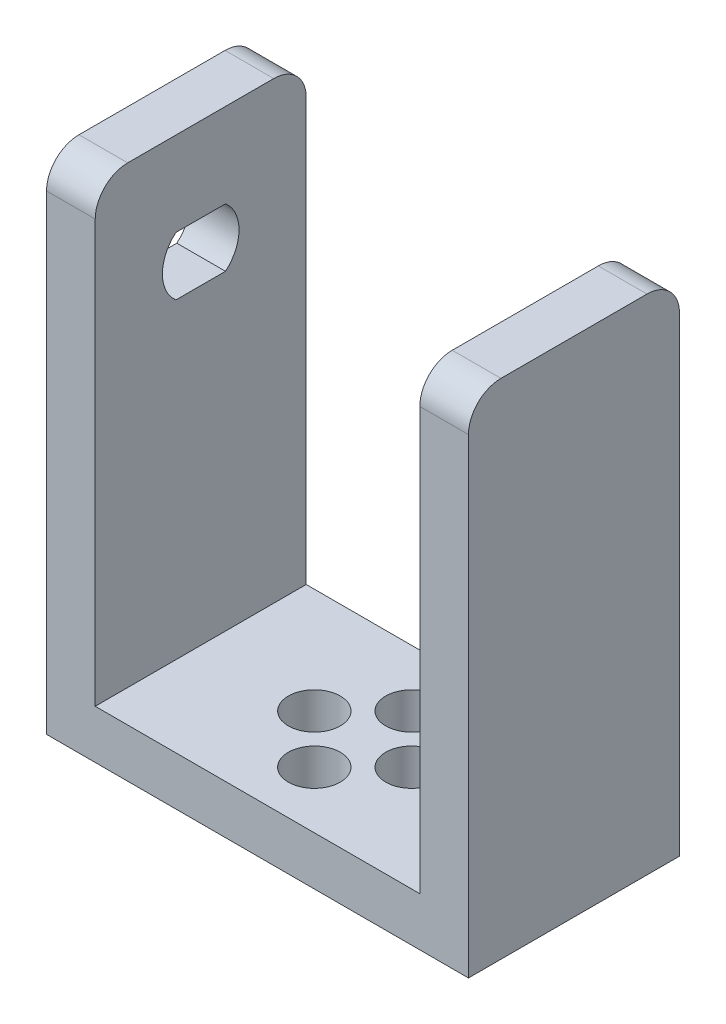
SolidWorks part; units mm, degrees
ref_plane "前视基准面" through (0, 0, 0) normal (0, 0, 1) x (1, 0, 0)
ref_plane "上视基准面" through (0, 0, 0) normal (0, 1, 0) x (1, 0, 0)
ref_plane "右视基准面" through (0, 0, 0) normal (1, 0, 0) x (0, 0, -1)
sketch "草图1" plane through (0, 0, 0) normal (0, 1, 0) x (1, 0, 0)
  line L0 (0, 0) -> (6.5796, 0) construction
  line L1 (-10, -6.5) -> (10, -6.5)
  line L2 (-10, -6.5) -> (-10, 6.5)
  line L3 (-10, 6.5) -> (10, 6.5)
  line L4 (10, -6.5) -> (10, 6.5)
  line L5 (-10, -6.5) -> (10, 6.5) construction
  line L6 (-10, 6.5) -> (10, -6.5) construction
  line L7 (0, 0) -> (0, 5.5116) construction
  circle A0 centre (0, 3) radius 1.6
  circle A1 centre (3, 0) radius 1.6
  circle A2 centre (0, -3) radius 1.6
  circle A3 centre (-3, 0) radius 1.6
  point P0 (0, 0)
  dimension "D3" = 3
  dimension "D1" = 13
  dimension "D2" = 20
  dimension "D4" = 3
extrude "凸台-拉伸1" add sketch "草图1" along normal blind 3
sketch "草图2" plane through (0, 0, 0) normal (0, 1, 0) x (1, 0, 0)
  line L0 (13, 6.5) -> (13, -6.5)
  line L1 (0, 0) -> (0, 7.5299) construction
  line L2 (10, 6.5) -> (10, 7.8287) construction
  line L3 (10, 6.5) -> (13, 6.5)
  line L4 (10, -6.5) -> (13, -6.5)
  line L5 (-10, -6.5) -> (-13, -6.5)
  line L6 (-13, 6.5) -> (-13, -6.5)
  line L7 (-10, 6.5) -> (-13, 6.5)
  line L8 (-10, 6.5) -> (-10, -6.5)
  line L9 (10, 6.5) -> (10, -6.5)
  dimension "D1" = 3
extrude "凸台-拉伸2" add sketch "草图2" along normal blind 31
sketch "草图3" plane through (10, 0, 0) normal (-1, 0, 0) x (0, 0, 1)
  line L0 (6.5, 0) -> (-6.5, 0) construction
  circle A0 centre (0, 24) radius 4.13
  dimension "D1" = 24
extrude "切除-拉伸1" cut sketch "草图3" against normal blind 1.5
sketch "草图4" plane through (-10, 0, 0) normal (1, 0, 0) x (0, 0, -1)
  line L0 (6.5, 0) -> (-6.5, 0) construction
  line L1 (1.5263, 25.8) -> (-1.5263, 25.8)
  line L2 (0, 24) -> (-1.5027, 24) construction
  line L3 (1.5263, 22.2) -> (-1.5263, 22.2)
  arc A0 (-1.5263, 25.8) -> (-1.5263, 22.2) centre (0, 24) ccw
  arc A1 (1.5263, 22.2) -> (1.5263, 25.8) centre (0, 24) ccw
  dimension "D2" = 1.8
  dimension "D3" = 1.8
  dimension "D1" = 24
extrude "切除-拉伸2" cut sketch "草图4" against normal blind 10
fillet "圆角1" radius 2 4 edges at (11.5, 31, -6.5) (11.5, 31, 6.5) (-11.5, 31, 6.5) (-11.5, 31, -6.5)
